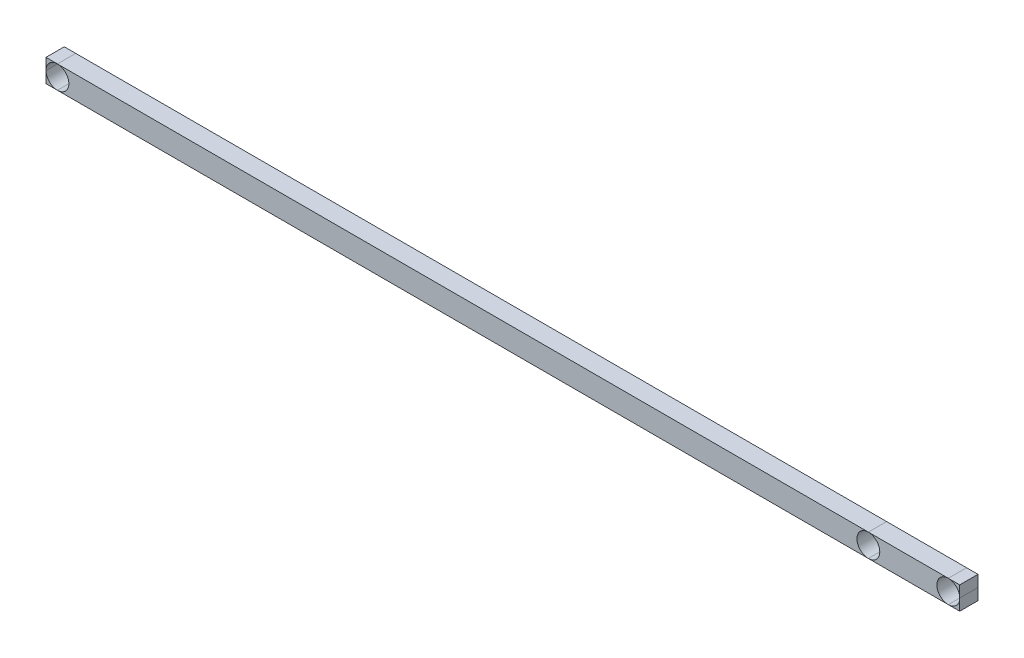
SolidWorks part; units mm, degrees
ref_plane "Front Plane" through (0, 0, 0) normal (0, 0, 1) x (1, 0, 0)
ref_plane "Top Plane" through (0, 0, 0) normal (0, 1, 0) x (1, 0, 0)
ref_plane "Right Plane" through (0, 0, 0) normal (1, 0, 0) x (0, 0, -1)
sketch "Sketch1" plane through (0, 0, 0) normal (0, 0, 1) x (1, 0, 0)
  line L0 (0, 0) -> (200, 0)
  line L1 (0, 0) -> (0, -5)
  line L2 (0, -5) -> (200, -5)
  line L3 (200, -5) -> (200, 0)
  dimension "D1" = 200
  dimension "D2" = 5
extrude "Boss-Extrude1" add sketch "Sketch1" along normal blind 4
sketch "Sketch2" plane through (0, 0, 4) normal (0, 0, 1) x (1, 0, 0)
  line L0 (200, 0) -> (0, 0) construction
  line L1 (0, 0) -> (0, -5) construction
  line L2 (200, -5) -> (200, 0) construction
  circle A0 centre (180, -2.5) radius 2.5
  circle A1 centre (2.5, -2.5) radius 2.5
  circle A2 centre (197.5, -2.5) radius 2.5
  dimension "D1" = 5
  dimension "D2" = 5
  dimension "D3" = 5
  dimension "D4" = 180
extrude "Cut-Extrude1" cut sketch "Sketch2" against normal blind 10
sketch "Sketch3" plane through (0, 0, 4) normal (0, 0, 1) x (1, 0, 0)
